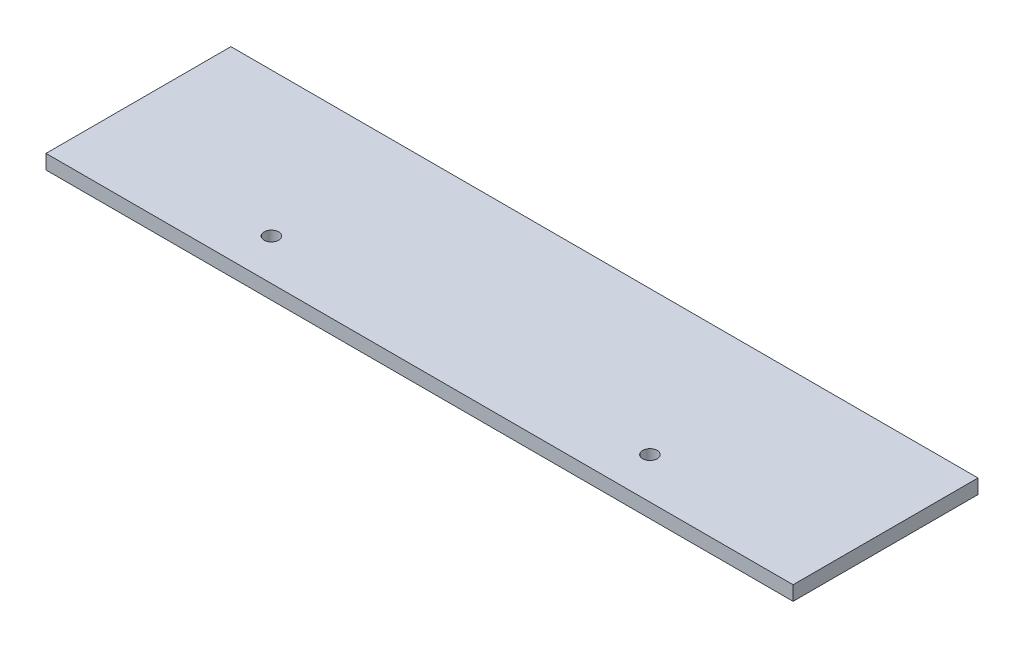
SolidWorks part; units mm, degrees
ref_plane "Front Plane" through (0, 0, 0) normal (0, 0, 1) x (1, 0, 0)
ref_plane "Top Plane" through (0, 0, 0) normal (0, 1, 0) x (1, 0, 0)
ref_plane "Right Plane" through (0, 0, 0) normal (1, 0, 0) x (0, 0, -1)
sketch "Sketch1" plane through (0, 0, 0) normal (0, 1, 0) x (1, 0, 0)
  line L1 (0, 0) -> (153.9436, 0)
  line L2 (0, 0) -> (0, 38.1)
  line L3 (0, 38.1) -> (153.9436, 38.1)
  line L4 (153.9436, 0) -> (153.9436, 38.1)
  circle A0 centre (37.9718, 8.4718) radius 1.5
  circle A1 centre (115.9718, 8.4718) radius 1.5
  point P9 (0, 0)
  dimension "D3" = 3
  dimension "D1" = 38.1
  dimension "D2" = 153.9436
  dimension "D4" = 8.4718
  dimension "D5" = 37.9718
  dimension "D6" = 37.9718
extrude "Boss-Extrude1" add sketch "Sketch1" along normal blind 2.9718
